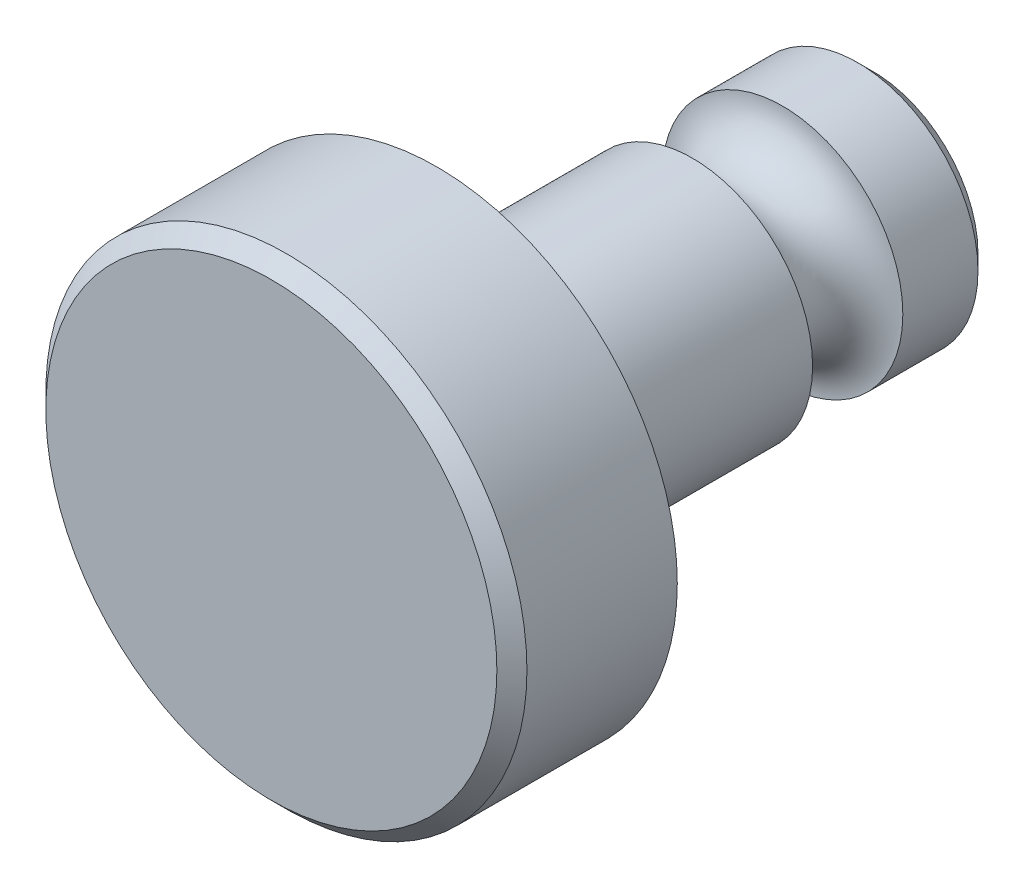
SolidWorks part; units mm, degrees
ref_plane "Front Plane" through (0, 0, 0) normal (0, 0, 1) x (1, 0, 0)
ref_plane "Top Plane" through (0, 0, 0) normal (0, 1, 0) x (1, 0, 0)
ref_plane "Right Plane" through (0, 0, 0) normal (1, 0, 0) x (0, 0, -1)
sketch "Sketch1" plane through (0, 0, 0) normal (1, 0, 0) x (0, 0, -1)
  line L1 (0, 0) -> (5.5, 0)
  line L2 (0, 0) -> (0, 8)
  line L3 (0, 8) -> (5.5, 8)
  line L4 (5.5, 0) -> (5.5, 8)
  line L5 (0, 0) -> (5.5, 8) construction
  line L6 (0, 8) -> (5.5, 0) construction
  line L7 (5.5, 4) -> (20, 4)
  line L8 (5.5, 4) -> (5.5, 0)
  line L9 (5.5, 0) -> (20, 0)
  line L10 (20, 4) -> (20, 0)
  line L11 (5.5, 4) -> (20, 0) construction
  line L12 (5.5, 0) -> (20, 4) construction
  circle A0 centre (15.5, 4) radius 1.5
  point P4 (2.75, 4)
  point P9 (12.75, 2)
  dimension "D5" = 10
  dimension "D1" = 5.5
  dimension "D2" = 8
  dimension "D3" = 4
  dimension "D4" = 14.5
revolve "Revolve1" add sketch "Sketch1" angle 360 about L9
chamfer "Chamfer1" distance 0.5 angle 45 1 edges at (8, 0, 0)
chamfer "Chamfer2" distance 0.5 angle 45 1 edges at (4, 0, -20)
